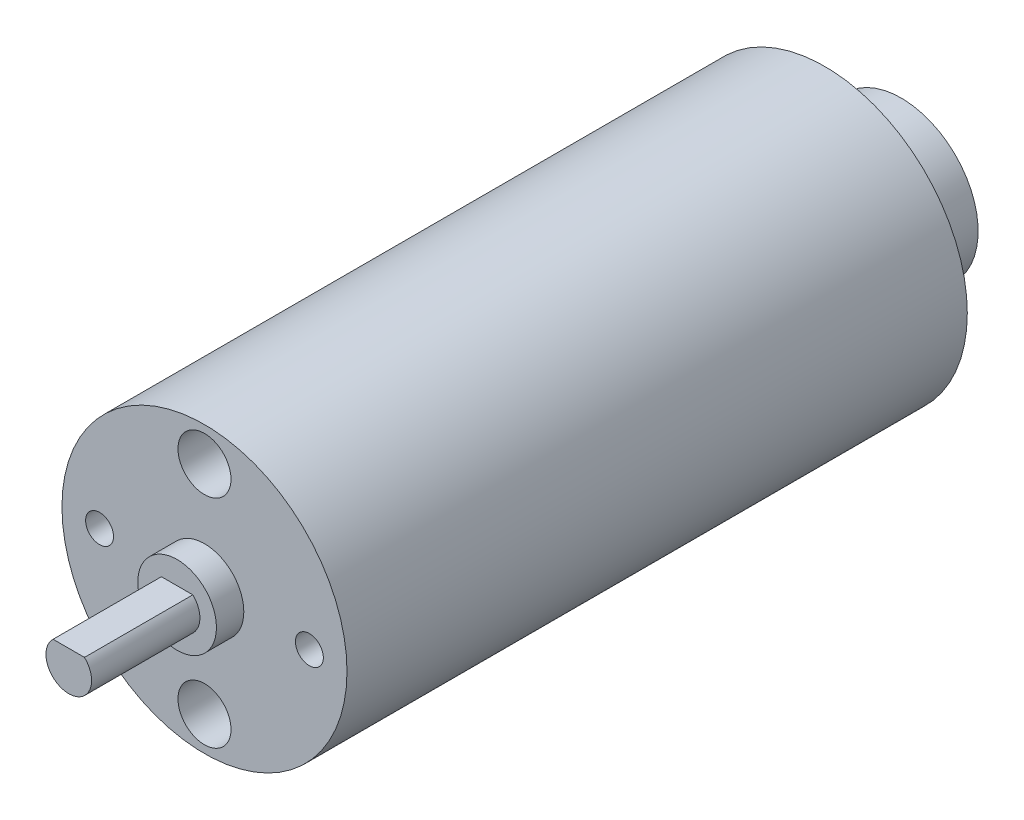
SolidWorks part; units mm, degrees
ref_plane "Front Plane" through (0, 0, 0) normal (0, 0, 1) x (1, 0, 0)
ref_plane "Top Plane" through (0, 0, 0) normal (0, 1, 0) x (1, 0, 0)
ref_plane "Right Plane" through (0, 0, 0) normal (1, 0, 0) x (0, 0, -1)
sketch "Sketch1" plane through (0, 0, 0) normal (0, 0, 1) x (1, 0, 0)
  circle A0 centre (0, 0) radius 12.5
  dimension "D1" = 25
extrude "Boss-Extrude1" add sketch "Sketch1" along normal blind 54.4
sketch "Sketch2" plane through (0, 0, 54.4) normal (0, 0, 1) x (1, 0, 0)
  circle A0 centre (0, 0) radius 3.45
  dimension "D1" = 6.9
extrude "Boss-Extrude2" add sketch "Sketch2" along normal blind 2.4
sketch "Sketch3" plane through (0, 0, 56.8) normal (0, 0, 1) x (1, 0, 0)
  circle A0 centre (0, 0) radius 2
  dimension "D1" = 4
extrude "Boss-Extrude3" add sketch "Sketch3" along normal blind 9.5
sketch "Sketch4" plane through (0, 0, 66.3) normal (0, 0, 1) x (1, 0, 0)
  line L5 (-3.1428, 4.2298) -> (3.1305, 4.2298)
  line L6 (-3.1428, 4.2298) -> (-3.1428, 1.45)
  line L7 (-3.1428, 1.45) -> (3.1305, 1.45)
  line L8 (3.1305, 4.2298) -> (3.1305, 1.45)
  circle A0 centre (0, 0) radius 3.45 construction
  dimension "D1" = 2.7798
  dimension "D2" = 6.2733
  dimension "D3" = 1.45
extrude "Cut-Extrude1" cut sketch "Sketch4" against normal blind 9.5
sketch "Sketch5" plane through (0, 0, 54.4) normal (0, 0, 1) x (1, 0, 0)
  line L0 (0, 0) -> (0, 12.5) construction
  circle A0 centre (0, 0) radius 12.5 construction
  circle A1 centre (0, 9.5) radius 2.325
  circle A2 centre (0, -9.5) radius 2.325
  point P13 (0, 0)
  dimension "D3" = 4.65
  dimension "D1" = 3
  dimension "D2" = 2
extrude "Cut-Extrude2" cut sketch "Sketch5" against normal blind 4.45
sketch "Sketch6" plane through (0, 0, 54.4) normal (0, 0, 1) x (1, 0, 0)
  line L0 (0, 0) -> (12.5, 0) construction
  circle A0 centre (0, 0) radius 12.5 construction
  circle A1 centre (9.2, 0) radius 1.225
  circle A2 centre (-9.2, 0) radius 1.225
  point P12 (0, 0)
  dimension "D1" = 2.45
  dimension "D2" = 3.3
  dimension "D3" = 2
extrude "Cut-Extrude3" cut sketch "Sketch6" against normal blind 4.45
sketch "Sketch8" plane through (0, 0, 0) normal (0, 0, -1) x (-1, 0, 0)
  circle A0 centre (0, 0) radius 1
  dimension "D1" = 2
extrude "Boss-Extrude5" add sketch "Sketch8" along normal blind 7.7
sketch "Sketch9" plane through (0, 0, 0) normal (0, 0, -1) x (-1, 0, 0)
  circle A0 centre (0, 0) radius 6.75
  dimension "D1" = 13.5
extrude "Boss-Extrude6" add sketch "Sketch9" along normal blind 6.7
sketch "Sketch10" plane through (0, 0, 0) normal (0, 0, -1) x (-1, 0, 0)
  circle A0 centre (0, 0) radius 6.75
extrude "Cut-Extrude5" cut sketch "Sketch10" along normal blind 2.2
sketch "Sketch11" plane through (0, 0, 0) normal (0, 0, -1) x (-1, 0, 0)
  circle A1 centre (0, 0) radius 1
extrude "Boss-Extrude7" add sketch "Sketch11" along normal blind 2.2
